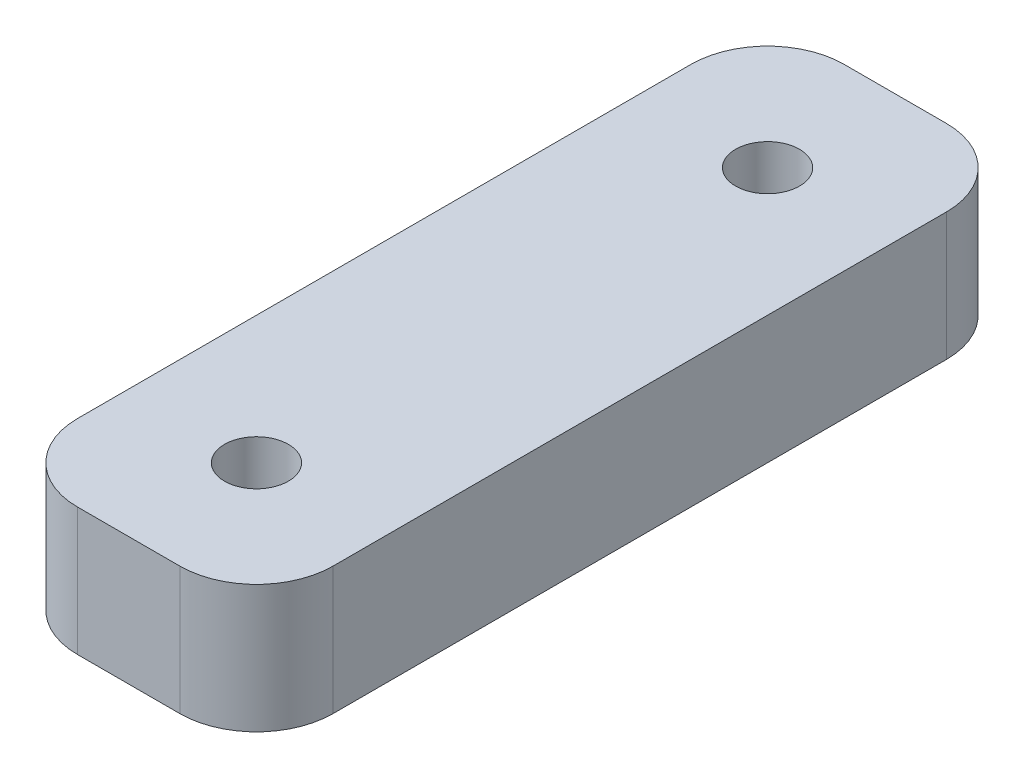
SolidWorks part; units mm, degrees
material "Oak"
ref_plane "Front Plane" through (0, 0, 0) normal (0, 0, 1) x (1, 0, 0)
ref_plane "Top Plane" through (0, 0, 0) normal (0, 1, 0) x (1, 0, 0)
ref_plane "Right Plane" through (0, 0, 0) normal (1, 0, 0) x (0, 0, -1)
sketch "Sketch1" plane through (0, 0, 0) normal (0, 1, 0) x (1, 0, 0)
  line L5 (3, 0) -> (13, 0)
  line L6 (3, 0) -> (3, 30)
  line L7 (3, 30) -> (13, 30)
  line L8 (13, 0) -> (13, 30)
  circle A0 centre (8, 25) radius 1.25
  circle A1 centre (8, 5) radius 1.25
  dimension "D3" = 2.5
  dimension "D6" = 2.5
  dimension "D1" = 30
  dimension "D2" = 10
  dimension "D4" = 5
  dimension "D5" = 5
  dimension "D7" = 5
  dimension "D8" = 5
extrude "Boss-Extrude1" add sketch "Sketch1" along normal blind 5
fillet "Fillet1" radius 3 4 edges at (13, 2.5, -30) (3, 2.5, -30) (13, 2.5, 0) (3, 2.5, 0)
